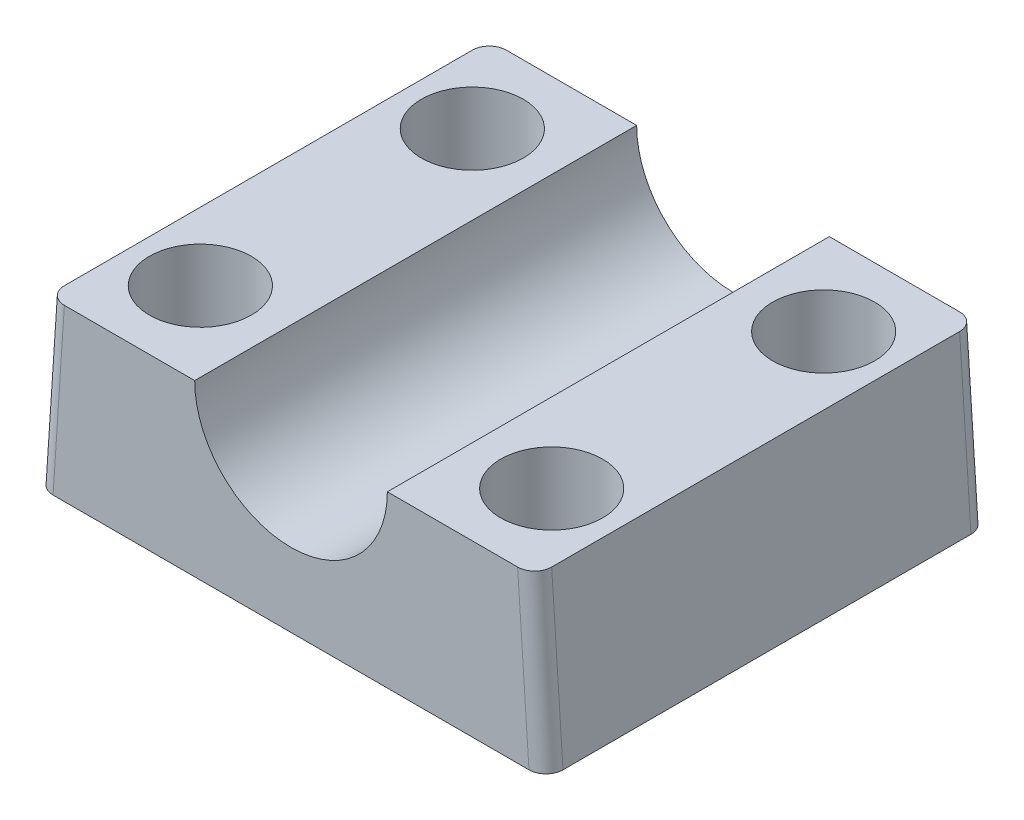
SolidWorks part; units mm, degrees
material "ABS"
ref_plane "Piano frontale" through (0, 0, 0) normal (0, 0, 1) x (1, 0, 0)
ref_plane "Piano superiore" through (0, 0, 0) normal (0, 1, 0) x (1, 0, 0)
ref_plane "Piano destro" through (0, 0, 0) normal (1, 0, 0) x (0, 0, -1)
sketch "Schizzo1" plane through (0, 0, 0) normal (0, 0, 1) x (1, 0, 0)
  line L0 (-8.5, 15) -> (-21.5, 15)
  line L1 (-21.5, 15) -> (-22.5, 0)
  line L2 (-22.5, 0) -> (22.5, 0)
  line L3 (22.5, 0) -> (21.5, 15)
  line L4 (21.5, 15) -> (8.5, 15)
  line L5 (0, 15) -> (0, 0) construction
  arc A0 (-8.5, 15) -> (8.5, 15) centre (0, 15) ccw
  dimension "D1" = 17
  dimension "D2" = 45
  dimension "D3" = 15
  dimension "D4" = 43
extrude "Estrusione-Estrusione1" add sketch "Schizzo1" along normal blind 39
sketch "Schizzo3" plane through (0, 0, 0) normal (0, -1, 0) x (-1, 0, 0)
  line L0 (-15.5, -7.5) -> (-15.5, -31.5) construction
  line L1 (-15.5, -31.5) -> (15.5, -31.5) construction
  line L2 (15.5, -31.5) -> (15.5, -7.5) construction
  line L3 (15.5, -7.5) -> (-15.5, -7.5) construction
  line L5 (22.5, 0) -> (-22.5, 0) construction
  point P0 (-15.5, -7.5)
  point P2 (15.5, -7.5)
  point P4 (15.5, -31.5)
  point P6 (-15.5, -31.5)
  dimension "D1" = 31
  dimension "D2" = 24
  dimension "D3" = 7.5
  dimension "D4" = 15.5
hole_wizard "Foro per Vite M8-1" positions "Schizzo3" profile "Schizzo4" hole size "M8" standard "ISO"
sketch "Schizzo4" plane through (15.5, 0, 7.5) normal (1, 0, 0) x (0, 0, -1)
  line L0 (0, 0) -> (0, 32.7039)
  line L1 (0, 32.7039) -> (4.5, 30)
  line L2 (4.5, 30) -> (4.5, 0)
  line L5 (4.5, 0) -> (0, 0)
  line L10 (0, 32.7039) -> (-4.5, 30) construction
  line L11 (0, -6.35) -> (0, 107.95) construction
  dimension "Hole Dia." = 9
  dimension "Hole Depth" = 30
  dimension "Drill Angle" = 118
fillet "Raccordo1" radius 1.5 4 edges at (22, 7.5, 39) (-22, 7.5, 39) (-22, 7.5, 0) (22, 7.5, 0)
